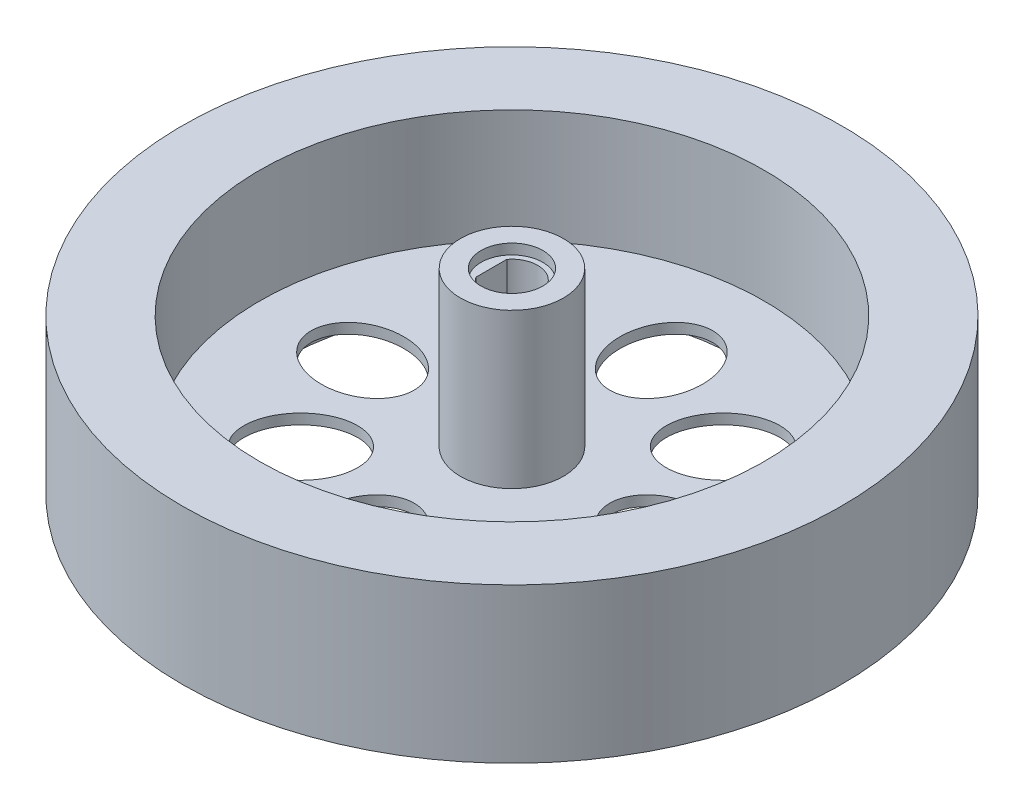
SolidWorks part; units mm, degrees
ref_plane "Front Plane" through (0, 0, 0) normal (0, 0, 1) x (1, 0, 0)
ref_plane "Top Plane" through (0, 0, 0) normal (0, 1, 0) x (1, 0, 0)
ref_plane "Right Plane" through (0, 0, 0) normal (1, 0, 0) x (0, 0, -1)
sketch "Sketch1" plane through (0, 0, 0) normal (0, 1, 0) x (1, 0, 0)
  circle A0 centre (0, 0) radius 32
  dimension "D1" = 64
extrude "Boss-Extrude1" add sketch "Sketch1" along normal blind 15 contours A0
sketch "Sketch2" plane through (0, 0, 0) normal (0, -1, 0) x (1, 0, 0)
  circle A0 centre (0, 0) radius 22.5
  dimension "D1" = 45
extrude "Cut-Extrude1" cut sketch "Sketch2" against normal blind 3
sketch "Sketch3" plane through (0, 3, 0) normal (0, -1, 0) x (1, 0, 0)
  circle A0 centre (0, 0) radius 7.5
  dimension "D1" = 15
extrude "Boss-Extrude2" add sketch "Sketch3" along normal blind 2
sketch "Sketch4" plane through (0, 15, 0) normal (0, 1, 0) x (1, 0, 0)
  circle A0 centre (0, 0) radius 24.5
  dimension "D1" = 49
extrude "Cut-Extrude2" cut sketch "Sketch4" against normal blind 11 contours A0
sketch "Sketch5" plane through (0, 4, 0) normal (0, 1, 0) x (1, 0, 0)
  circle A0 centre (0, 0) radius 5
  dimension "D1" = 10
extrude "Boss-Extrude3" add sketch "Sketch5" along normal blind 15
sketch "Sketch6" plane through (0, 4, 0) normal (0, 1, 0) x (1, 0, 0)
  line L0 (0, 0) -> (0, -24.5) construction
  line L1 (0, -24.5) -> (24.5, 0) construction
  circle A0 centre (0, 0) radius 24.5 construction
  circle A1 centre (0, 0) radius 24.5 construction
  ellipse E0 centre (0, -14.5) end of major axis (0, -19.5) minor radius 4
  ellipse E1 centre (-10.253, -10.253) end of major axis (-13.7886, -13.7886) minor radius 4
  ellipse E2 centre (-14.5, 0) end of major axis (-19.5, 0) minor radius 4
  ellipse E3 centre (-10.253, 10.253) end of major axis (-13.7886, 13.7886) minor radius 4
  ellipse E4 centre (0, 14.5) end of major axis (0, 19.5) minor radius 4
  ellipse E5 centre (10.253, 10.253) end of major axis (6.7175, 6.7175) minor radius 4
  ellipse E6 centre (14.5, 0) end of major axis (19.5, 0) minor radius 4
  ellipse E7 centre (10.253, -10.253) end of major axis (13.7886, -13.7886) minor radius 4
  dimension "D1" = 8
  dimension "D2" = 10
  dimension "D3" = 10
extrude "Cut-Extrude3" cut sketch "Sketch6" against normal through all
sketch "Sketch7" plane through (0, 19, 0) normal (0, 1, 0) x (1, 0, 0)
  circle A0 centre (0, 0) radius 3
  dimension "D1" = 6
extrude "Cut-Extrude4" cut sketch "Sketch7" against normal blind 1
sketch "Sketch8" plane through (0, 18, 0) normal (0, 1, 0) x (1, 0, 0)
  line L0 (0, 0) -> (0, -2.5) construction
  line L1 (0, -2.5) -> (2.5, 0) construction
  line L2 (2.5, 0) -> (0, 0) construction
  line L3 (2, -1.5) -> (2, 1.5)
  line L4 (-2, -1.5) -> (-2, 1.5)
  arc A0 (-2, -1.5) -> (2, -1.5) centre (0, 0) ccw
  arc A1 (2, 1.5) -> (-2, 1.5) centre (0, 0) ccw
  point P7 (1.884, 0)
  point P8 (2.0064, 0)
  point P10 (2, 0)
  dimension "D1" = 5
  dimension "D2" = 2
extrude "Cut-Extrude5" cut sketch "Sketch8" against normal blind 7
